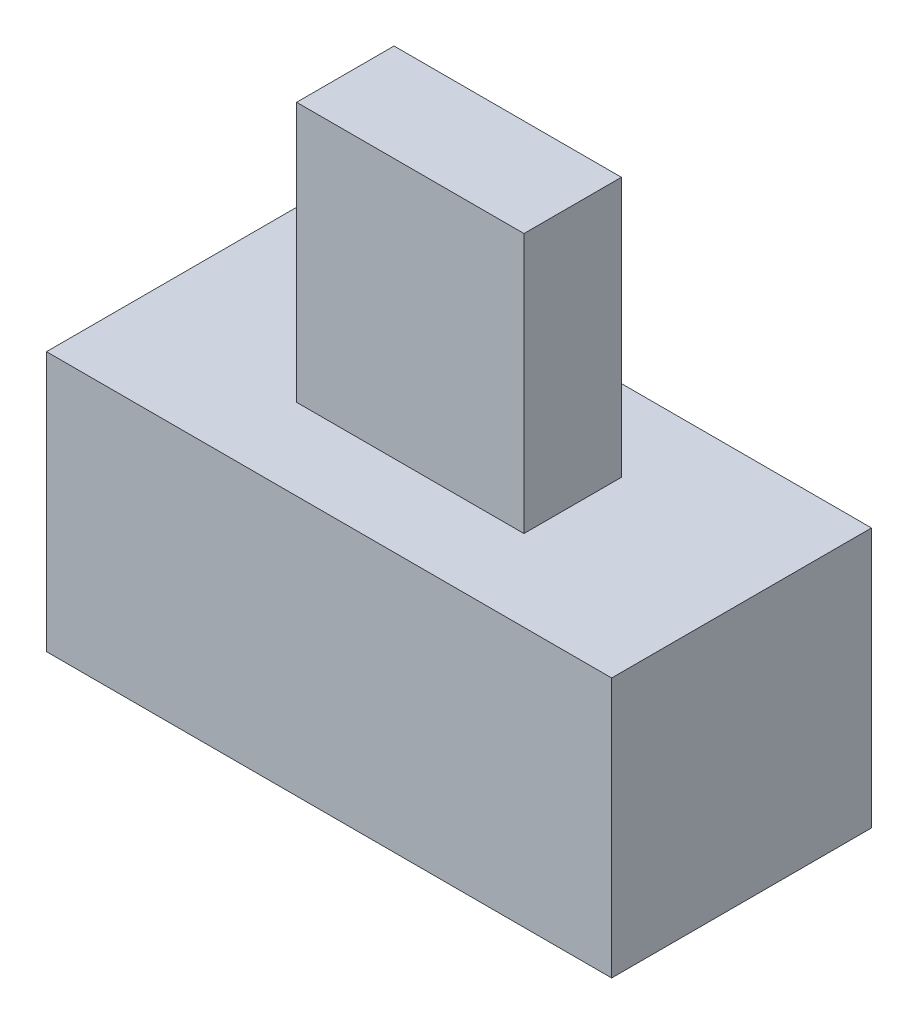
SolidWorks part; units mm, degrees
ref_plane "Front Plane" through (0, 0, 0) normal (0, 0, 1) x (1, 0, 0)
ref_plane "Top Plane" through (0, 0, 0) normal (0, 1, 0) x (1, 0, 0)
ref_plane "Right Plane" through (0, 0, 0) normal (1, 0, 0) x (0, 0, -1)
sketch "Sketch1" plane through (0, 0, 0) normal (0, 1, 0) x (1, 0, 0)
  line L1 (0, 0) -> (8.7, 0)
  line L2 (0, 0) -> (0, 4)
  line L3 (0, 4) -> (8.7, 4)
  line L4 (8.7, 0) -> (8.7, 4)
  dimension "D1" = 8.7
  dimension "D2" = 4
extrude "Boss-Extrude1" add sketch "Sketch1" along normal blind 4
sketch "Sketch2" plane through (0, 4, 0) normal (0, 1, 0) x (1, 0, 0)
  line L0 (8.7, 0) -> (8.7, 4) construction
  line L1 (2.6, 2.75) -> (6.1, 2.75)
  line L2 (2.6, 2.75) -> (2.6, 1.25)
  line L3 (2.6, 1.25) -> (6.1, 1.25)
  line L4 (6.1, 2.75) -> (6.1, 1.25)
  line L5 (8.7, 4) -> (0, 4) construction
  point P4 (6.1, 2)
  point P7 (8.7, 2)
  point P8 (4.35, 2.75)
  point P11 (4.35, 4)
  dimension "D1" = 1.5
  dimension "D2" = 3.5
extrude "Boss-Extrude2" add sketch "Sketch2" along normal blind 4
